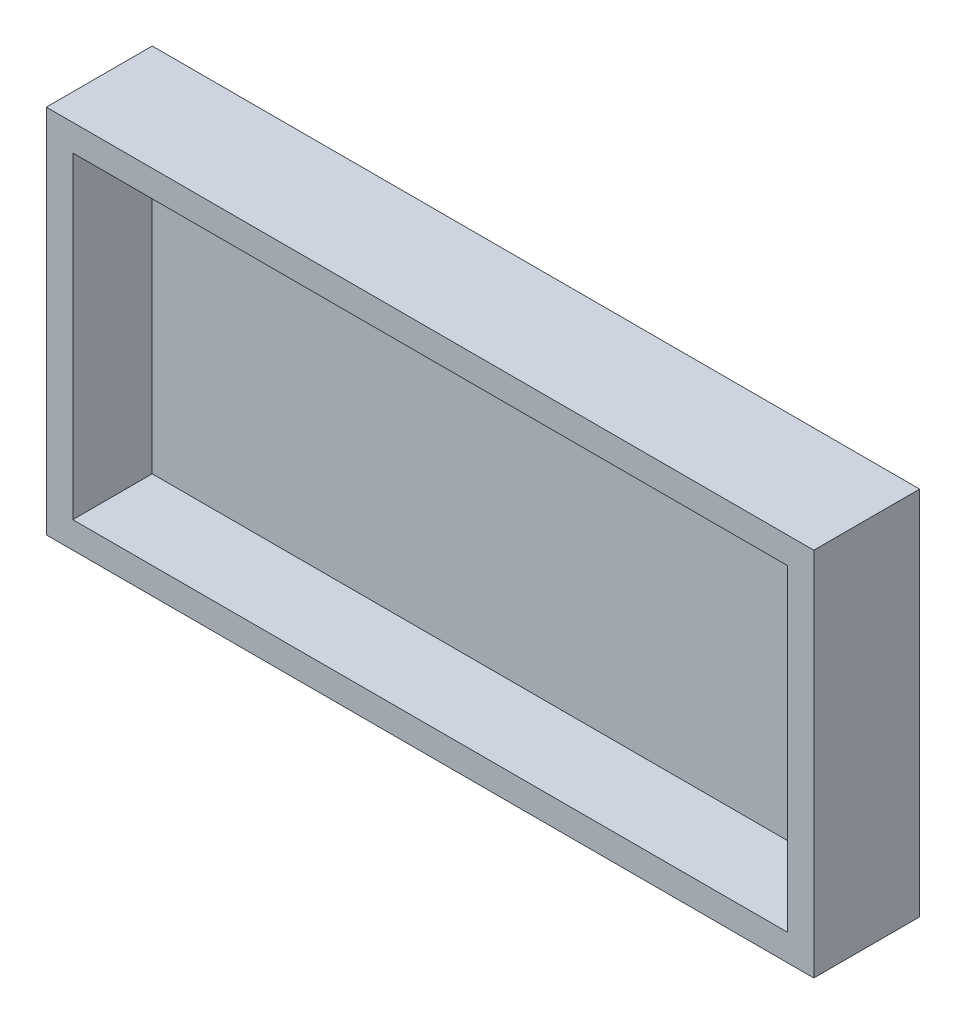
SolidWorks part; units mm, degrees
ref_plane "Alzado" through (0, 0, 0) normal (0, 0, 1) x (1, 0, 0)
ref_plane "Planta" through (0, 0, 0) normal (0, 1, 0) x (1, 0, 0)
ref_plane "Vista lateral" through (0, 0, 0) normal (1, 0, 0) x (0, 0, -1)
sketch "Croquis1" plane through (0, 0, 0) normal (0, 0, 1) x (1, 0, 0)
  line L1 (-29, 14) -> (29, 14)
  line L2 (-29, 14) -> (-29, -14)
  line L3 (-29, -14) -> (29, -14)
  line L4 (29, 14) -> (29, -14)
  line L5 (-29, 14) -> (29, -14) construction
  line L6 (-29, -14) -> (29, 14) construction
  point P0 (0, 0)
  dimension "D1" = 28
  dimension "D2" = 58
extrude "Saliente-Extruir1" add sketch "Croquis1" along normal blind 2
sketch "Croquis2" plane through (0, 0, 2) normal (0, 0, 1) x (1, 0, 0)
  line L1 (-29, 14) -> (29, 14)
  line L2 (-29, 14) -> (-29, -14)
  line L3 (-29, -14) -> (29, -14)
  line L4 (29, 14) -> (29, -14)
  line L5 (-29, 14) -> (29, -14) construction
  line L6 (-29, -14) -> (29, 14) construction
  line L7 (-27, 12) -> (27, 12)
  line L8 (-27, 12) -> (-27, -12)
  line L9 (-27, -12) -> (27, -12)
  line L10 (27, 12) -> (27, -12)
  line L11 (-27, 12) -> (27, -12) construction
  line L12 (-27, -12) -> (27, 12) construction
  point P0 (0, 0)
  point P7 (0, 0)
  dimension "D1" = 2
  dimension "D2" = 2
  dimension "D3" = 2
extrude "Saliente-Extruir2" add sketch "Croquis2" along normal blind 6
